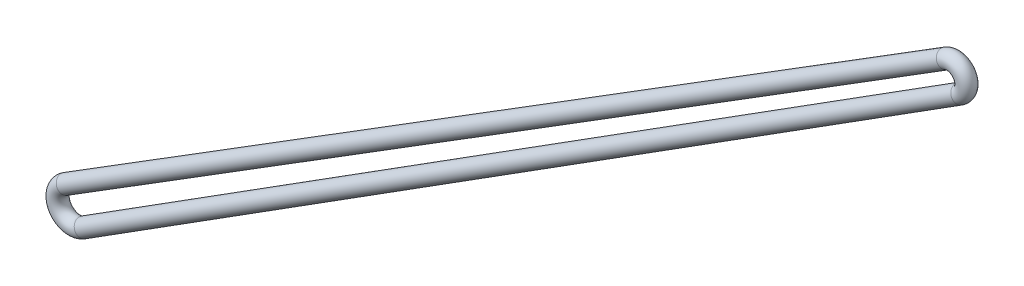
SolidWorks part; units mm, degrees
ref_plane "前视基准面" through (0, 0, 0) normal (0, 0, 1) x (1, 0, 0)
ref_plane "上视基准面" through (0, 0, 0) normal (0, 1, 0) x (1, 0, 0)
ref_plane "右视基准面" through (0, 0, 0) normal (1, 0, 0) x (0, 0, -1)
sketch "草图2" plane through (0, 0, 0) normal (0, 0, 1) x (1, 0, 0)
  line L0 (0, 0) -> (1, 0) construction
  line L1 (0, 0) -> (0, 1) construction
  line L2 (-1.6399, 2.6307) -> (159.5984, 103.1387)
  line L3 (162.2568, 98.904) -> (1.6565, -2.6203)
  arc A0 (1.6565, -2.6203) -> (-1.6399, 2.6307) centre (0, 0) cw
  arc A1 (159.5984, 103.1387) -> (162.2568, 98.904) centre (160.9209, 101.0171) cw
sweep "扫描1" add path "草图2" circular profile diameter 3 parameters "D3"=3
